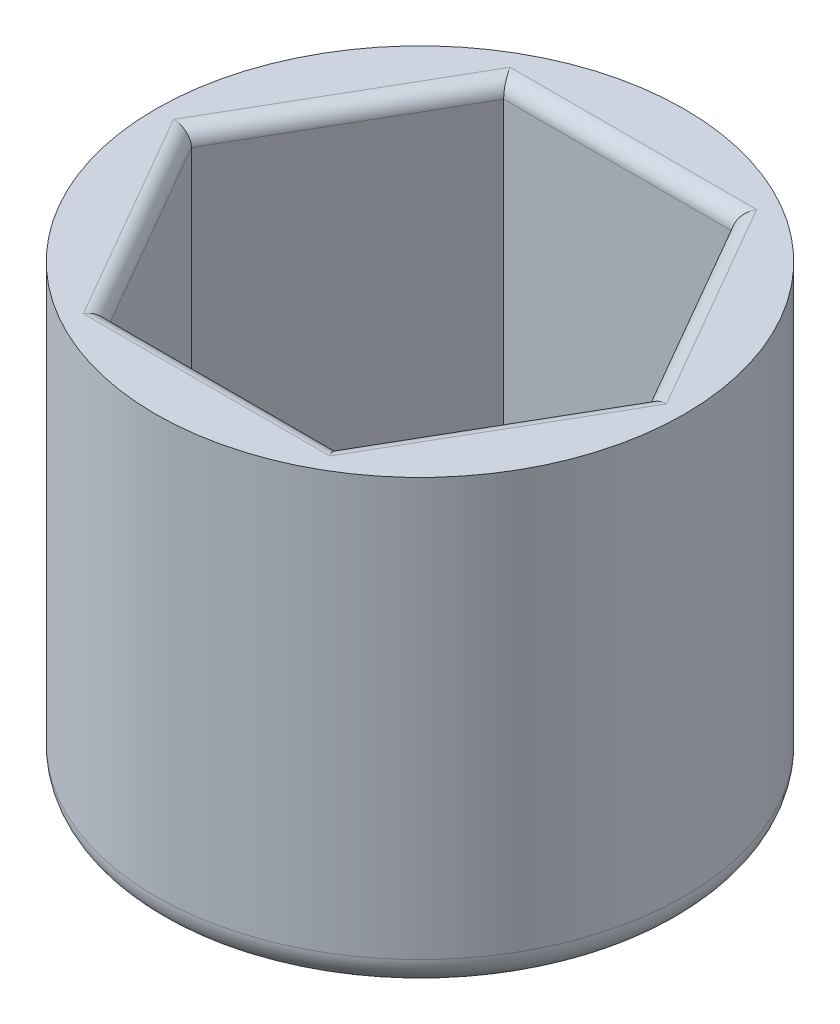
SolidWorks part; units mm, degrees
ref_plane "Alzado" through (0, 0, 0) normal (0, 0, 1) x (1, 0, 0)
ref_plane "Planta" through (0, 0, 0) normal (0, 1, 0) x (1, 0, 0)
ref_plane "Vista lateral" through (0, 0, 0) normal (1, 0, 0) x (0, 0, -1)
sketch "Croquis1" plane through (0, 0, 0) normal (0, 1, 0) x (1, 0, 0)
  line L0 (8.5448, 0) -> (4.2724, 7.4)
  line L1 (-3.695, 6.4) -> (-7.3901, 0)
  line L2 (-7.3901, 0) -> (-3.695, -6.4)
  line L3 (-3.695, -6.4) -> (3.695, -6.4)
  line L4 (3.695, -6.4) -> (7.3901, 0)
  line L5 (7.3901, 0) -> (3.695, 6.4)
  line L6 (3.695, 6.4) -> (-3.695, 6.4)
  line L7 (4.2724, 7.4) -> (-4.2724, 7.4)
  line L8 (-4.2724, 7.4) -> (-8.5448, 0)
  line L9 (-8.5448, 0) -> (-4.2724, -7.4)
  line L10 (-4.2724, -7.4) -> (4.2724, -7.4)
  line L11 (4.2724, -7.4) -> (8.5448, 0)
  circle A0 centre (0, 0) radius 6.4 construction
  dimension "D1" = 12.8
  dimension "D2" = 1
extrude "Saliente-Extruir1" add sketch "Croquis1" along normal blind 12
sketch "Croquis2" plane through (0, 0, 0) normal (0, -1, 0) x (1, 0, 0)
  line L6 (8.5448, 0) -> (4.2724, 7.4)
  line L7 (4.2724, 7.4) -> (-4.2724, 7.4)
  line L8 (-4.2724, 7.4) -> (-8.5448, 0)
  line L9 (-8.5448, 0) -> (-4.2724, -7.4)
  line L10 (-4.2724, -7.4) -> (4.2724, -7.4)
  line L11 (4.2724, -7.4) -> (8.5448, 0)
  line L12 (8.5448, 0) -> (4.2724, 7.4)
  line L13 (4.2724, 7.4) -> (-4.2724, 7.4)
  line L14 (-4.2724, 7.4) -> (-8.5448, 0)
  line L15 (-8.5448, 0) -> (-4.2724, -7.4)
  line L16 (-4.2724, -7.4) -> (4.2724, -7.4)
  line L17 (4.2724, -7.4) -> (8.5448, 0)
  dimension "D1" = 0
extrude "Saliente-Extruir2" add sketch "Croquis2" along normal blind 2.5
fillet "Redondeo2" radius 0.5 6 edges at (0, 12, 6.4) (-5.5426, 12, 3.2) (-5.5426, 12, -3.2) (0, 12, -6.4) (5.5426, 12, -3.2) (5.5426, 12, 3.2)
sketch "Croquis3" plane through (0, -2.5, 0) normal (0, -1, 0) x (1, 0, 0)
  line L0 (-4.2724, -7.4) -> (4.2724, -7.4) construction
  line L1 (4.2724, -7.4) -> (8.5448, 0) construction
  line L2 (8.5448, 0) -> (4.2724, 7.4) construction
  line L3 (4.2724, 7.4) -> (-4.2724, 7.4) construction
  line L4 (-4.2724, 7.4) -> (-8.5448, 0) construction
  line L5 (-8.5448, 0) -> (-4.2724, -7.4) construction
  line L6 (-4.2724, -7.4) -> (4.2724, -7.4)
  line L7 (4.2724, -7.4) -> (8.5448, 0)
  line L8 (8.5448, 0) -> (4.2724, 7.4)
  line L9 (4.2724, 7.4) -> (-4.2724, 7.4)
  line L10 (-4.2724, 7.4) -> (-8.5448, 0)
  line L11 (-8.5448, 0) -> (-4.2724, -7.4)
  circle A0 centre (0, 0) radius 8.5448
  line M1 (4.2724, -7.4) -> (8.5448, 0)
  line M2 (8.5448, 0) -> (4.2724, 7.4)
  line M3 (4.2724, 7.4) -> (-4.2724, 7.4)
  line M4 (-4.2724, 7.4) -> (-8.5448, 0)
  line M5 (-8.5448, 0) -> (-4.2724, -7.4)
  line M6 (-4.2724, -7.4) -> (4.2724, -7.4)
extrude "Saliente-Extruir4" add sketch "Croquis3" against normal up to surface (14.5 mm away) contours A0 M2 | A0 M3 | A0 M4 | A0 M5 | A0 M6 | A0 M1 up to face at (0, 12, 0)
fillet "Redondeo5" radius 1 1 edges at (0, -2.5, -8.5448)
